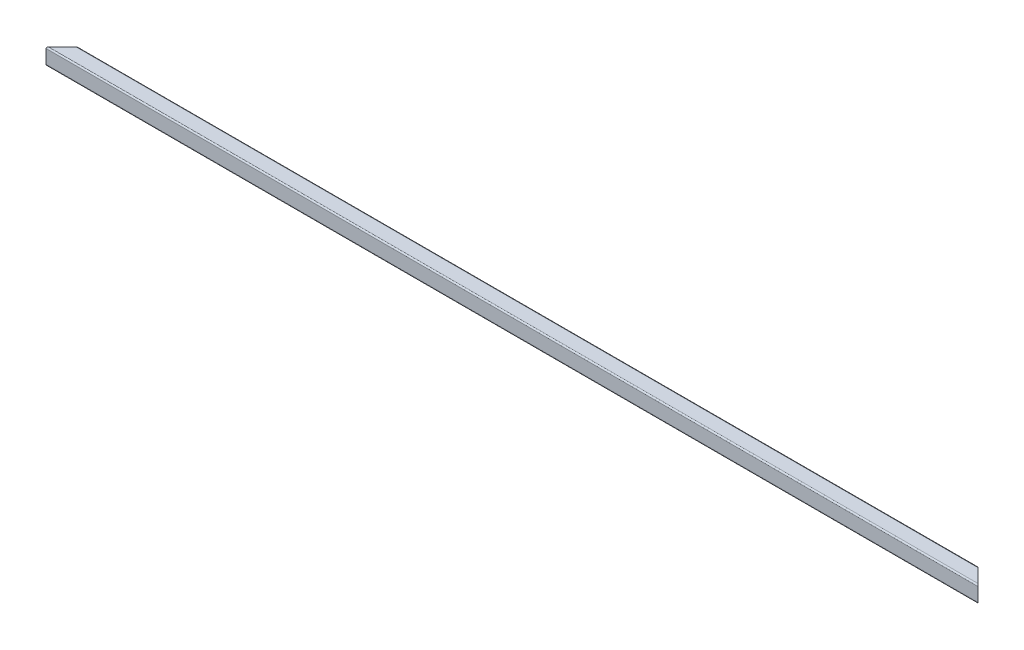
SolidWorks part; units mm, degrees
material "Plain Carbon Steel"
ref_plane "Front Plane" through (0, 0, 0) normal (0, 0, 1) x (1, 0, 0)
ref_plane "Top Plane" through (0, 0, 0) normal (0, 1, 0) x (1, 0, 0)
ref_plane "Right Plane" through (0, 0, 0) normal (1, 0, 0) x (0, 0, -1)
sketch "Sketch1" plane through (0, 0, 0) normal (1, 0, 0) x (0, 0, -1)
  line L0 (0, 2.54) -> (0, 29.21)
  line L1 (-2.54, 31.75) -> (-29.21, 31.75)
  line L2 (-31.75, 29.21) -> (-31.75, 2.54)
  line L3 (-29.21, 0) -> (-2.54, 0)
  line L4 (-4.1275, 4.1275) -> (-4.1275, 27.6225)
  line L5 (-4.1275, 27.6225) -> (-27.6225, 27.6225)
  line L6 (-27.6225, 27.6225) -> (-27.6225, 4.1275)
  line L7 (-27.6225, 4.1275) -> (-4.1275, 4.1275)
  arc A0 (-31.75, 2.54) -> (-29.21, 0) centre (-29.21, 2.54) ccw
  arc A1 (0, 2.54) -> (-2.54, 0) centre (-2.54, 2.54) cw
  arc A2 (0, 29.21) -> (-2.54, 31.75) centre (-2.54, 29.21) ccw
  arc A3 (-31.75, 29.21) -> (-29.21, 31.75) centre (-29.21, 29.21) cw
  arc A4 (-4.1275, 27.6225) -> (-4.1275, 27.6225) centre (-4.1275, 27.6225) ccw
  arc A5 (-27.6225, 27.6225) -> (-27.6225, 27.6225) centre (-27.6225, 27.6225) cw
  arc A6 (-27.6225, 4.1275) -> (-27.6225, 4.1275) centre (-27.6225, 4.1275) ccw
  arc A7 (-4.1275, 4.1275) -> (-4.1275, 4.1275) centre (-4.1275, 4.1275) cw
  point P12 (0, 0)
  point P15 (0, 31.75)
  point P18 (-31.75, 31.75)
  dimension "D3" = 2.54
  dimension "D1" = 31.75
  dimension "D2" = 31.75
  dimension "D4" = 4.1275
extrude "Boss-Extrude1" add sketch "Sketch1" along normal blind 723.9
scale "Scale1" scale about centroid uniform scaling no x scale factor 1 y scale factor 0.4 z scale factor 0.4
sketch "Sketch2" plane through (0, 0, 22.225) normal (0, 0, -1) x (-1, 0, 0)
  line L0 (-723.9, 9.525) -> (0, 9.525) construction
  point P4 (-361.95, 9.525)
sketch "Sketch3" plane through (0, 22.225, 0) normal (0, 1, 0) x (1, 0, 0)
  line L0 (0, -22.225) -> (12.7, -22.225) construction
  line L7 (12.7, -22.225) -> (12.7, -9.525) construction
  line L8 (6.35, -22.225) -> (6.35, -9.525) construction
  line L12 (723.9, -22.225) -> (0, -22.225) construction
  line L13 (361.95, -10.541) -> (361.95, -21.209) construction
  line L14 (723.9, -10.541) -> (0, -10.541) construction
  line L15 (723.9, -21.209) -> (0, -21.209) construction
  line L19 (0, -10.541) -> (0, -21.209) construction
  line L21 (0, -9.525) -> (0, -22.225)
  line L22 (0, -15.875) -> (6.35, -15.875) construction
  line L26 (0, -9.525) -> (0, -10.541) construction
  line L27 (6.35, -15.875) -> (12.7, -15.875) construction
  line L28 (0, -22.225) -> (12.7, -9.525)
  line L29 (12.7, -9.525) -> (0, -9.525)
  line L33 (723.9, -9.525) -> (723.9, -22.225)
  line L34 (723.9, -9.525) -> (0, -9.525) construction
  line L35 (723.9, -22.225) -> (711.2, -9.525)
  line L36 (711.2, -9.525) -> (723.9, -9.525)
  point P6 (6.35, -15.875)
  point P9 (12.7, -15.875)
  point P125 (6.35, -15.875)
  dimension "D1" = 12.7
  dimension "D2" = 12.7
  dimension "D3" = 12.7
extrude "Cut-Extrude1" cut sketch "Sketch3" against normal through all
